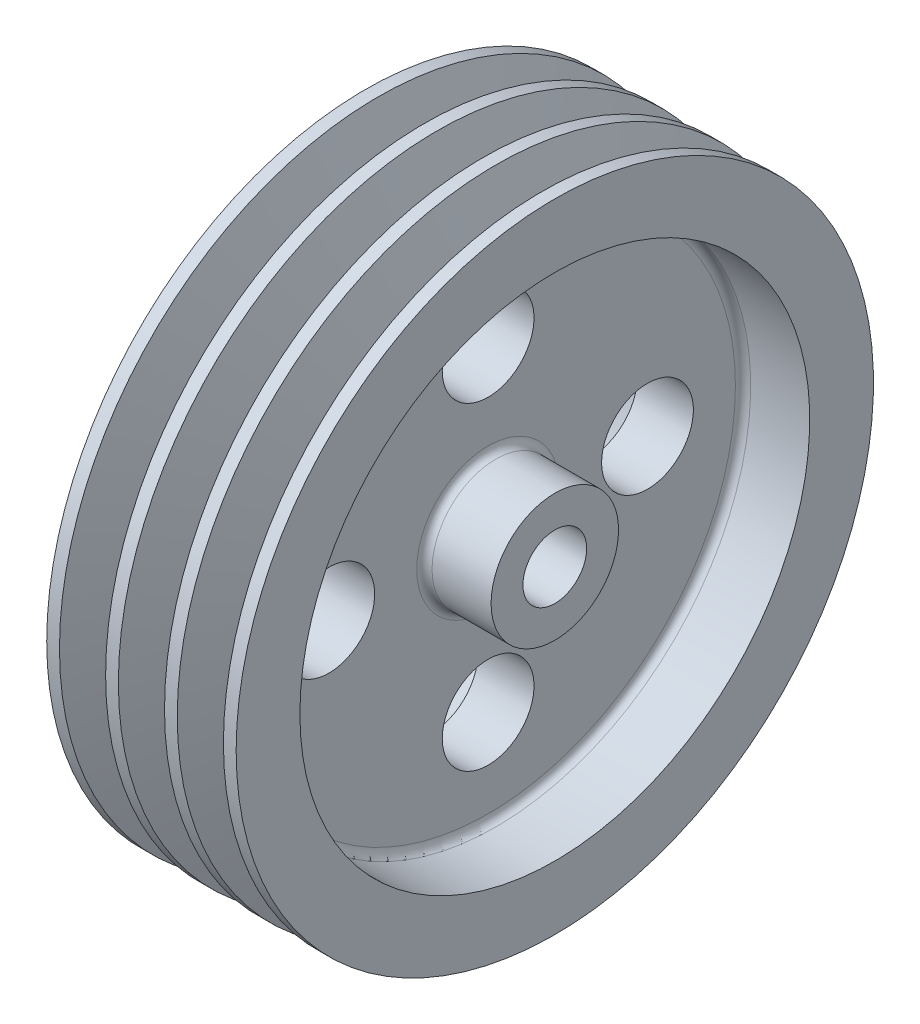
SolidWorks part; units mm, degrees
ref_plane "Front Plane" through (0, 0, 0) normal (0, 0, 1) x (1, 0, 0)
ref_plane "Top Plane" through (0, 0, 0) normal (0, 1, 0) x (1, 0, 0)
ref_plane "Right Plane" through (0, 0, 0) normal (1, 0, 0) x (0, 0, -1)
sketch "Sketch1" plane through (0, 0, 0) normal (0, 0, 1) x (1, 0, 0)
  line L0 (-37.1544, -12.5) -> (-14, -12.5)
  line L1 (-37.1544, -12.5) -> (-37.1544, 12.5)
  line L2 (37.1544, -12.5) -> (37.1544, 12.5)
  line L3 (37.1544, 12.5) -> (32.1544, 12.5)
  line L5 (25.6029, -5.5) -> (20.6029, -5.5)
  line L8 (11, -84.5) -> (11, -15.5)
  line L9 (2.5, -5.5) -> (9.0515, 12.5)
  line L10 (-34.1544, -87.5) -> (-14, -87.5)
  line L12 (-2.5, -5.5) -> (-9.0515, 12.5)
  line L13 (-32.1544, 12.5) -> (-25.6029, -5.5)
  line L14 (-14.0515, 12.5) -> (-20.6029, -5.5)
  line L15 (14.0515, 12.5) -> (20.6029, -5.5)
  line L16 (25.6029, -5.5) -> (32.1544, 12.5)
  line L17 (-20.6029, -5.5) -> (-25.6029, -5.5)
  line L18 (37.1544, -5.5) -> (-37.1544, -5.5) construction
  line L19 (-11, -84.5) -> (-11, -15.5)
  line L20 (2.5, -5.5) -> (-2.5, -5.5)
  line L21 (-9.0515, 12.5) -> (-14.0515, 12.5)
  line L22 (-32.1544, 12.5) -> (-37.1544, 12.5)
  line L23 (37.1544, 12.5) -> (-37.1544, 12.5) construction
  line L24 (14.0515, 12.5) -> (9.0515, 12.5)
  line L26 (-37.1544, -12.5) -> (37.1544, -12.5) construction
  line L28 (-37.1544, -87.5) -> (37.1544, -87.5) construction
  line L29 (37.1544, -87.5) -> (37.1544, -100)
  line L30 (-37.1544, -90.5) -> (-37.1544, -100)
  line L31 (14, -87.5) -> (37.1544, -87.5)
  line L32 (-37.1544, -100) -> (37.1544, -100)
  line L33 (14, -100) -> (37.1544, -100) construction
  line L34 (-92.4333, -112.5) -> (71.2177, -112.5) construction
  line L35 (14, -12.5) -> (37.1544, -12.5)
  arc A0 (-11, -15.5) -> (-14, -12.5) centre (-14, -15.5) ccw
  arc A1 (14, -12.5) -> (11, -15.5) centre (14, -15.5) ccw
  arc A2 (-11, -84.5) -> (-14, -87.5) centre (-14, -84.5) cw
  arc A3 (14, -87.5) -> (11, -84.5) centre (14, -84.5) cw
  arc A4 (-34.1544, -87.5) -> (-37.1544, -90.5) centre (-34.1544, -90.5) ccw
  point P2 (-53.8977, 5.1859)
  point P10 (61.5228, -3.6599)
  point P11 (2.4759, 12.5)
  point P12 (71.2177, -12.5)
  point P13 (-2.5241, 12.5)
  point P26 (0, 0)
  dimension "D22" = 3
  dimension "D23" = 3
  dimension "D24" = 3
  dimension "D25" = 3
  dimension "D27" = 3
  dimension "D7" = 5
  dimension "D3" = 12.5
  dimension "D5" = 40
  dimension "D6" = 2.5
  dimension "D8" = 9.0515
  dimension "D9" = 11
  dimension "D10" = 22
  dimension "D12" = 25
  dimension "D15" = 5
  dimension "D4" = 18
  dimension "D18" = 75
  dimension "D26" = 12.5
revolve "Revolve1" add sketch "Sketch1" angle 360 about L34
sketch "Sketch2" plane through (-11, 0, 0) normal (-1, 0, 0) x (0, 0, 1)
  circle A0 centre (0, -112.5) radius 62.5 construction
  circle A1 centre (0, -50) radius 18
  circle A2 centre (62.5, -112.5) radius 18
  circle A3 centre (0, -175) radius 18
  circle A4 centre (-62.5, -112.5) radius 18
  point P5 (0, 0)
  point P6 (0, 0)
  point P14 (0, -112.5)
  dimension "D1" = 125
  dimension "D2" = 36
  dimension "D4" = 88.3883
  dimension "D5" = 62.5
  dimension "D3" = 4
extrude "Cut-Extrude1" cut sketch "Sketch2" against normal blind 169 contours A4 | A3 | A2 | A1
